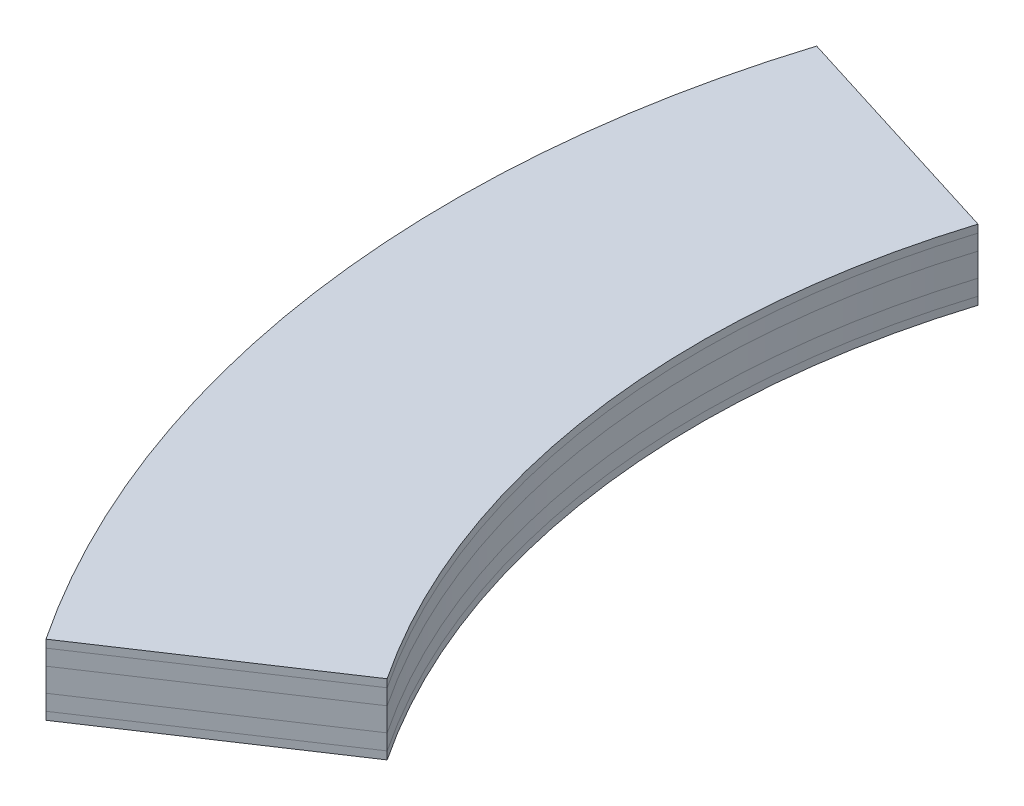
SolidWorks part; units mm, degrees
ref_plane "Front Plane" through (0, 0, 0) normal (0, 0, 1) x (1, 0, 0)
ref_plane "Top Plane" through (0, 0, 0) normal (0, 1, 0) x (1, 0, 0)
ref_plane "Right Plane" through (0, 0, 0) normal (1, 0, 0) x (0, 0, -1)
sketch "Sketch1" plane through (0, 0, 0) normal (0, 1, 0) x (1, 0, 0)
  line L0 (-304.8, 609.6) -> (304.8, 609.6) construction
  line L1 (304.8, 609.6) -> (304.8, -609.6) construction
  line L2 (0, 609.6) -> (0, 0) construction
  line L3 (0, 0) -> (304.8, 0) construction
  dimension "Width" = 609.6
  dimension "Length" = 1219.2
sketch "Sketch2" plane through (0, 0, 0) normal (1, 0, 0) x (0, 0, -1)
  line L0 (609.6, 0) -> (609.6, -25.4) construction
  dimension "Thickness" = 25.4
sketch "Sketch3" plane through (0, 0, 0) normal (0, 1, 0) x (1, 0, 0)
  line L1 (-304.8, 609.6) -> (304.8, 609.6)
  line L2 (-304.8, 609.6) -> (-304.8, -609.6)
  line L3 (-304.8, -609.6) -> (304.8, -609.6)
  line L4 (304.8, 609.6) -> (304.8, -609.6)
extrude "Boss-Extrude1" add sketch "Sketch3" against normal up to vertex (25.4 mm away) up to point (0, -25.4, -609.6)
sketch "Sketch4" plane through (0, 0, 0) normal (0, 0, 1) x (1, 0, 0)
  line L0 (0, -11.2889) -> (0, -14.1111) construction
  line L1 (-335.28, -22.5778) -> (335.28, -22.5778)
  line L2 (0, 0) -> (0, -25.4) construction
  line L3 (0, -11.2889) -> (0, -8.4667) construction
  line L4 (0, -14.1111) -> (0, -16.9333) construction
  line L5 (0, -8.4667) -> (0, -5.6444) construction
  line L6 (0, -5.6444) -> (0, -2.8222) construction
  line L7 (0, -2.8222) -> (0, 0) construction
  line L8 (0, -16.9333) -> (0, -19.7556) construction
  line L9 (0, -19.7556) -> (0, -22.5778) construction
  line L10 (0, -22.5778) -> (0, -25.4) construction
  line L11 (-335.28, -16.9333) -> (335.28, -16.9333)
  line L12 (-335.28, -2.8222) -> (335.28, -2.8222)
  line L13 (-335.28, -8.4667) -> (335.28, -8.4667)
  point P5 (0, -12.7)
  point P16 (0, -22.5778)
  point P19 (0, -16.9333)
  point P23 (0, -2.8222)
  point P25 (0, -8.4667)
  dimension "D1" = 670.56
split "Split1" trim tools "Sketch4" bodies to split 104 resulting bodies 105 106 107 108 109
sketch "Sketch6" plane through (0, 0, 0) normal (0, 1, 0) x (1, 0, 0)
  line L6 (-304.8, 609.6) -> (-304.8, -609.6)
  line L7 (-304.8, -609.6) -> (304.8, -609.6)
  line L8 (304.8, -609.6) -> (304.8, 609.6)
  line L9 (304.8, 609.6) -> (-304.8, 609.6)
  line L10 (46.2704, 282.4435) -> (131.1121, 255.89)
  line L11 (92.6124, -42.3162) -> (166.641, 6.9075)
  arc A0 (92.6124, -42.3162) -> (46.2704, 282.4435) centre (409.8778, 168.6427) cw
  arc A1 (166.641, 6.9075) -> (131.1121, 255.89) centre (409.8778, 168.6427) cw
  point P8 (0, 0)
  dimension "D1" = 381
  dimension "D4" = 0
  dimension "D2" = 88.9
  dimension "D3" = 88.9
extrude "Cut-Extrude1" cut sketch "Sketch6" against normal blind 25.4
equation "\"D1@Sketch4\"=\"Width@Sketch1\"*1.1"
